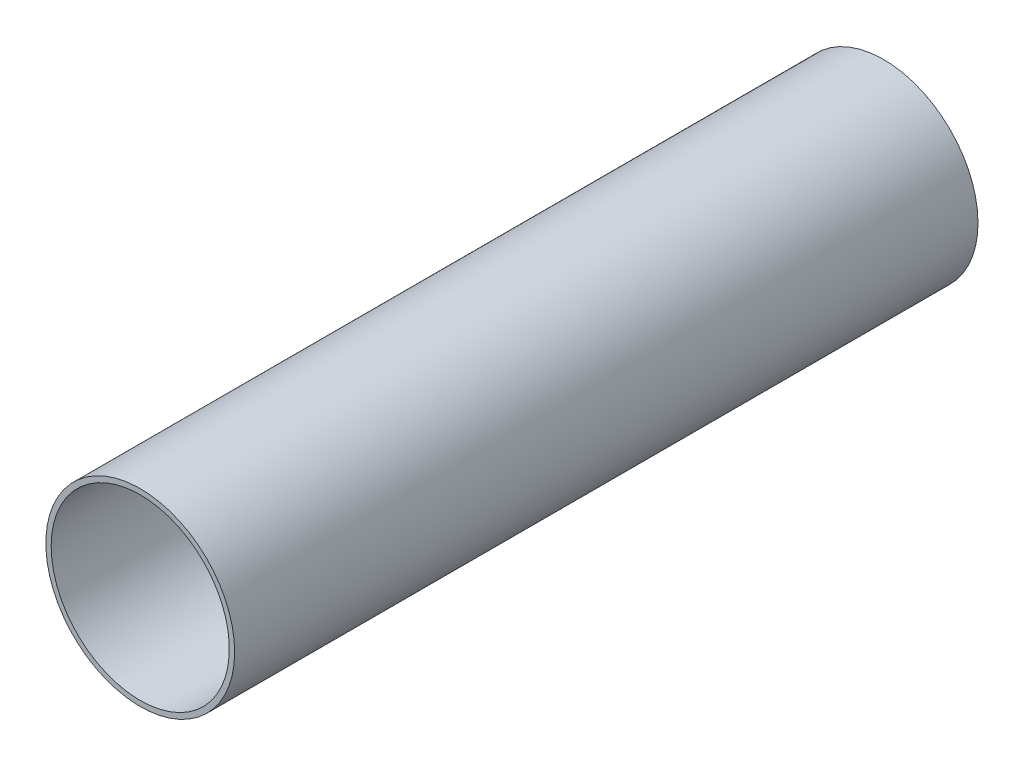
SolidWorks part; units mm, degrees
material "Cobre"
ref_plane "Alzado" through (0, 0, 0) normal (0, 0, 1) x (1, 0, 0)
ref_plane "Planta" through (0, 0, 0) normal (0, 1, 0) x (1, 0, 0)
ref_plane "Vista lateral" through (0, 0, 0) normal (1, 0, 0) x (0, 0, -1)
sketch "Croquis1" plane through (0, 0, 0) normal (0, 0, 1) x (1, 0, 0)
  circle A0 centre (0, 0) radius 19.05
extrude "Saliente-Extruir1" add sketch "Croquis1" along normal blind 150
sketch "Croquis2" plane through (0, 0, 0) normal (0, 0, -1) x (-1, 0, 0)
  circle A0 centre (0, 0) radius 17.9789
extrude "Cortar-Extruir1" cut sketch "Croquis2" against normal blind 150
